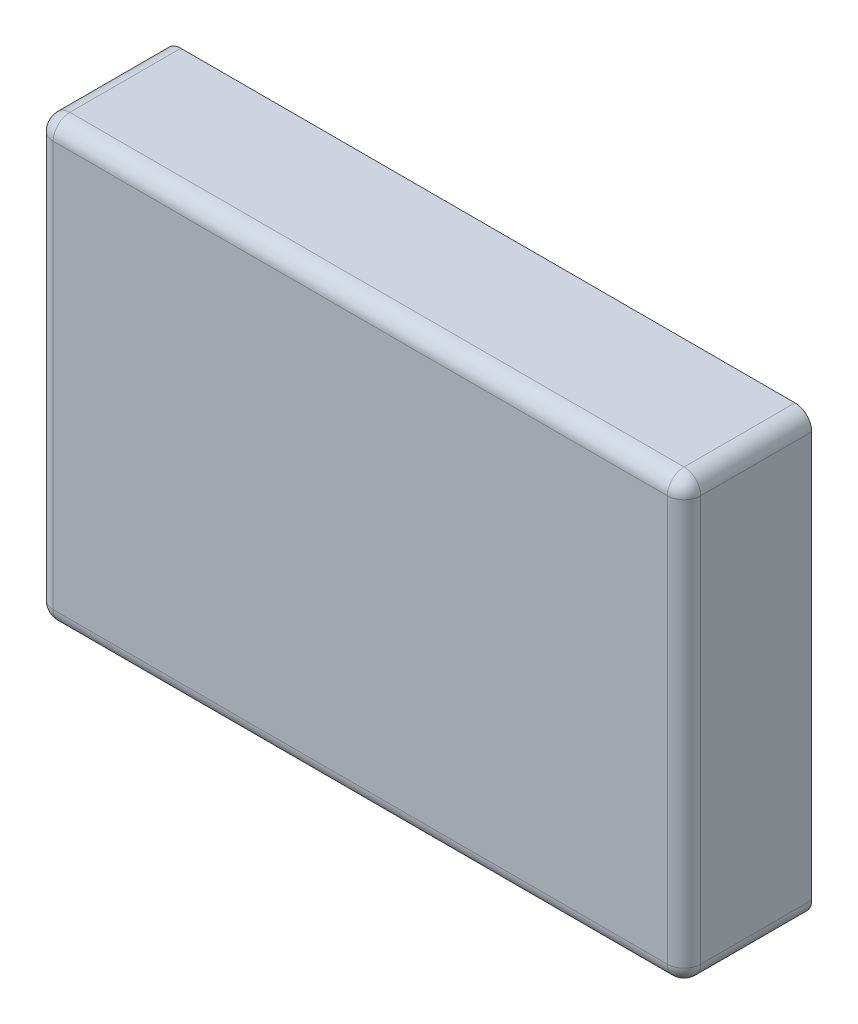
SolidWorks part; units mm, degrees
ref_plane "Front Plane" through (0, 0, 0) normal (0, 0, 1) x (1, 0, 0)
ref_plane "Top Plane" through (0, 0, 0) normal (0, 1, 0) x (1, 0, 0)
ref_plane "Right Plane" through (0, 0, 0) normal (1, 0, 0) x (0, 0, -1)
sketch "Sketch1" plane through (0, 0, 0) normal (0, 0, 1) x (1, 0, 0)
  line L1 (0, 0) -> (49.3522, 0)
  line L2 (0, 0) -> (0, 33.4518)
  line L3 (0, 33.4518) -> (49.3522, 33.4518)
  line L4 (49.3522, 0) -> (49.3522, 33.4518)
  dimension "D1" = 33.4518
  dimension "D2" = 49.3522
extrude "Boss-Extrude1" add sketch "Sketch1" along normal blind 9.7282
fillet "Fillet1" radius 1.27 8 edges at (24.6761, 33.4518, 9.7282) (49.3522, 16.7259, 9.7282) (24.6761, 0, 9.7282) (0, 16.7259, 9.7282) (0, 0, 4.8641) (49.3522, 0, 4.8641) (49.3522, 33.4518, 4.8641) (0, 33.4518, 4.8641)
